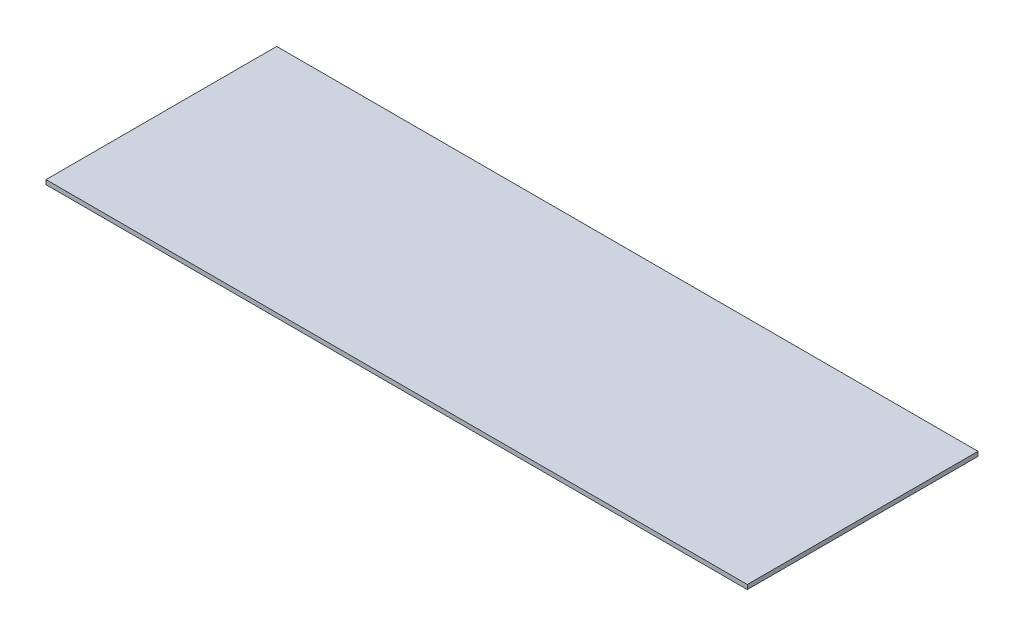
SolidWorks part; units mm, degrees
material "6061 Alloy"
ref_plane "Front" through (0, 0, 0) normal (0, 0, 1) x (1, 0, 0)
ref_plane "Top" through (0, 0, 0) normal (0, 1, 0) x (1, 0, 0)
ref_plane "Right" through (0, 0, 0) normal (1, 0, 0) x (0, 0, -1)
sketch "Sketch1" plane through (0, 0, 0) normal (0, 1, 0) x (1, 0, 0)
  line L1 (0, 0) -> (202.692, 0)
  line L2 (0, 0) -> (0, 66.675)
  line L3 (0, 66.675) -> (202.692, 66.675)
  line L4 (202.692, 0) -> (202.692, 66.675)
  dimension "D1" = 66.675
  dimension "D2" = 202.692
extrude "Boss-Extrude1" add sketch "Sketch1" along normal blind 1.27
